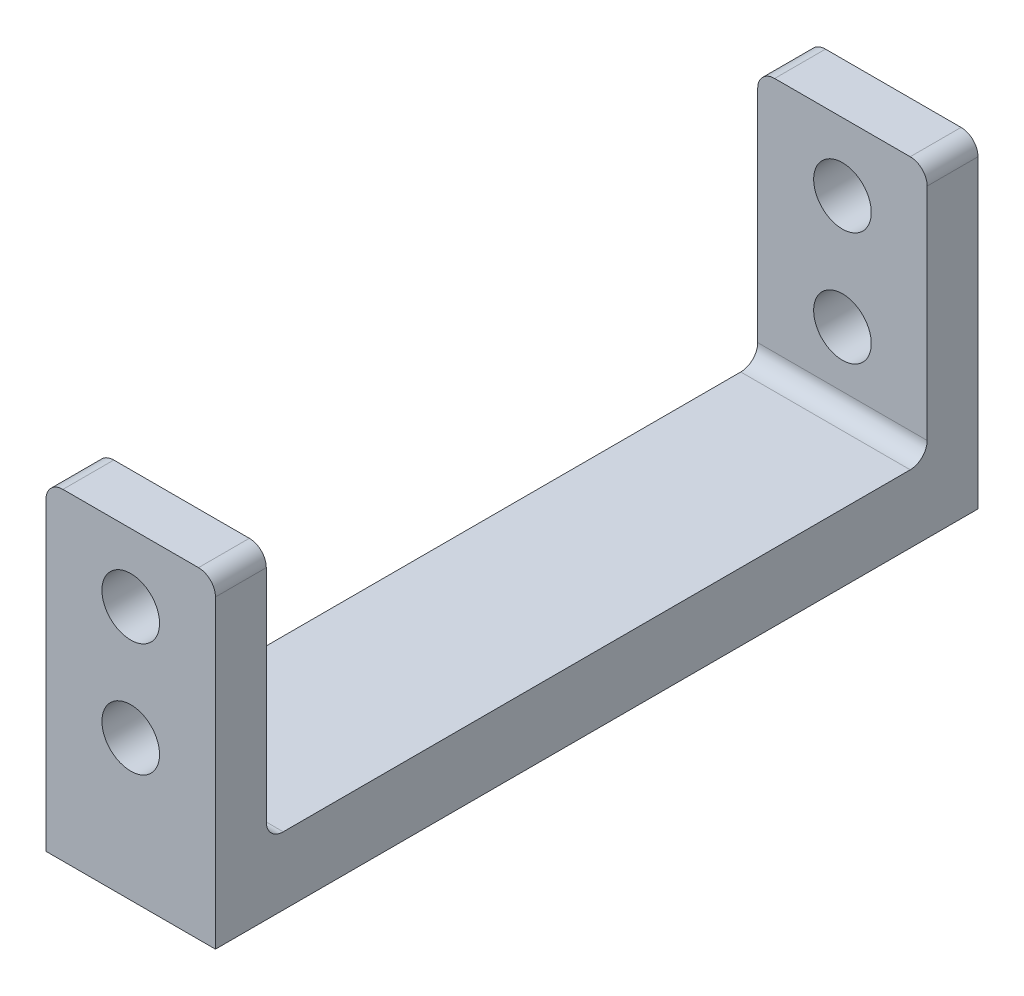
SolidWorks part; units mm, degrees
ref_plane "Front Plane" through (0, 0, 0) normal (0, 0, 1) x (1, 0, 0)
ref_plane "Top Plane" through (0, 0, 0) normal (0, 1, 0) x (1, 0, 0)
ref_plane "Right Plane" through (0, 0, 0) normal (1, 0, 0) x (0, 0, -1)
sketch "Sketch2" plane through (0, 0, 0) normal (0, 1, 0) x (1, 0, 0)
  line L3 (5, 22.5) -> (-5, 22.5)
  line L4 (5, 22.5) -> (5, -22.5)
  line L5 (5, -22.5) -> (-5, -22.5)
  line L6 (-5, 22.5) -> (-5, -22.5)
  line L7 (5, 22.5) -> (-5, -22.5) construction
  line L8 (5, -22.5) -> (-5, 22.5) construction
  point P0 (0, 0)
  dimension "D1" = 10
  dimension "D2" = 45
extrude "Boss-Extrude1" add sketch "Sketch2" along normal blind 4
sketch "Sketch3" plane through (0, 4, 0) normal (0, 1, 0) x (1, 0, 0)
  line L0 (5, -22.5) -> (5, 22.5) construction
  line L1 (-5, 22.5) -> (5, 22.5)
  line L2 (-5, 22.5) -> (-5, 19.5)
  line L3 (-5, 19.5) -> (5, 19.5)
  line L4 (5, 22.5) -> (5, 19.5)
  line L5 (-55, 0) -> (55, 0) construction
  line L6 (5, -22.5) -> (5, -19.5)
  line L7 (-5, -19.5) -> (5, -19.5)
  line L8 (-5, -22.5) -> (-5, -19.5)
  line L9 (-5, -22.5) -> (5, -22.5)
  dimension "D1" = 3
extrude "Boss-Extrude2" add sketch "Sketch3" along normal blind 15
hole_wizard "M3 Clearance Hole1" positions "3DSketch1" profile "Sketch4" hole size "M3" standard "ANSI Metric" end condition up to next
sketch3d "3DSketch1"
  line L0 (5, 19, -22.5) -> (5, 0, -22.5) construction
  line L1 (5, 19, -22.5) -> (-5, 19, -22.5) construction
  point P0 (0, 15, -22.5)
  point P2 (0, 8.3, -22.5)
  point P6 (0, 15, 22.5)
  point P10 (0, 8.3, 22.5)
  point P13 (0, 0, 0)
  point P14 (0, 0, 0)
  point P15 (0.2003, 8.2518, -22.5)
  point P16 (-0.1641, 7.5589, 22.5)
  point P19 (0, 0, 0)
  point P20 (0, 0, 0)
  point P21 (0, 0, 0)
  point P24 (0, 0, 0)
  point P25 (0, 0, 0)
  point P26 (0, 0, 0)
  dimension "D1" = 5
  dimension "D2" = 6.7
  dimension "D3" = 4
sketch "Sketch4" plane through (0, 15, -22.5) normal (1, 0, 0) x (0, 1, 0)
  line L0 (0, 0) -> (0, 3)
  line L1 (0, 3) -> (1.7, 3)
  line L2 (1.7, 3) -> (1.7, 0)
  line L5 (1.7, 0) -> (0, 0)
  line L11 (0, -6.35) -> (0, 107.95) construction
  dimension "Thru Hole Dia." = 3.4
  dimension "Thru Hole Depth" = 3
fillet "Fillet1" radius 1 6 edges at (0, 4, 19.5) (0, 4, -19.5) (5, 19, 21) (-5, 19, 21) (5, 19, -21) (-5, 19, -21)
